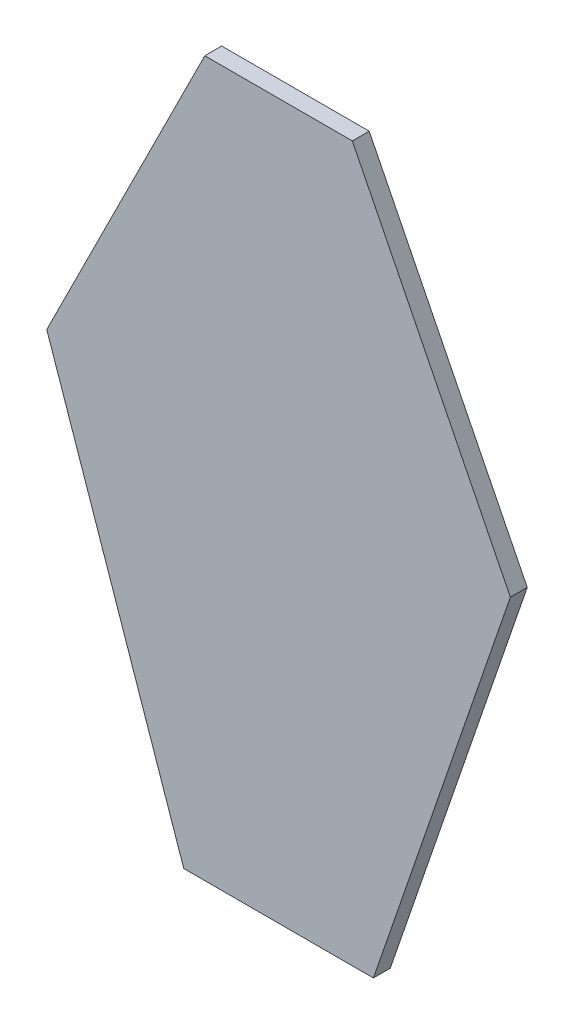
SolidWorks part; units mm, degrees
ref_plane "前视" through (0, 0, 0) normal (0, 0, 1) x (1, 0, 0)
ref_plane "上视" through (0, 0, 0) normal (0, 1, 0) x (1, 0, 0)
ref_plane "右视" through (0, 0, 0) normal (1, 0, 0) x (0, 0, -1)
sketch "草图1" plane through (0, 0, 0) normal (0, 0, 1) x (1, 0, 0)
  line L0 (-200.0754, 0) -> (200.6735, 0) construction
  line L2 (0, 0) -> (0, -800.5573) construction
  line L3 (-70, 228) -> (70, 228)
  line L4 (-70, 228) -> (-220, -72)
  line L5 (70, 228) -> (220, -72)
  line L6 (-90, -450) -> (90, -450)
  line L7 (-220, -72) -> (-90, -450)
  line L8 (220, -72) -> (90, -450)
  line L9 (-245.8942, -140) -> (333.011, -140) construction
  line L10 (-60, -414.9282) -> (-60, 484.23) construction
  line L11 (60, 458.938) -> (60, -204.0754) construction
  line L12 (-479.9392, 160) -> (333.011, 160) construction
  line L13 (-90, -240) -> (140, -240) construction
  line L14 (-90, -320) -> (262.5772, -320) construction
  line L15 (-90, -400) -> (60, -400) construction
  line L16 (56, -431.0616) -> (56, -227) construction
  point P8 (-220, -72)
  point P9 (220, -72)
  dimension "D17" = 68
  dimension "D18" = 56
  dimension "D1" = 140
  dimension "D2" = 228
  dimension "D3" = 300
  dimension "D4" = 220
  dimension "D5" = 678
  dimension "D6" = 180
  dimension "D7" = 140
  dimension "D9" = 60
  dimension "D12" = 100
  dimension "D15" = 80
  dimension "D16" = 80
extrude "基体-拉伸" add sketch "草图1" along normal blind 16
